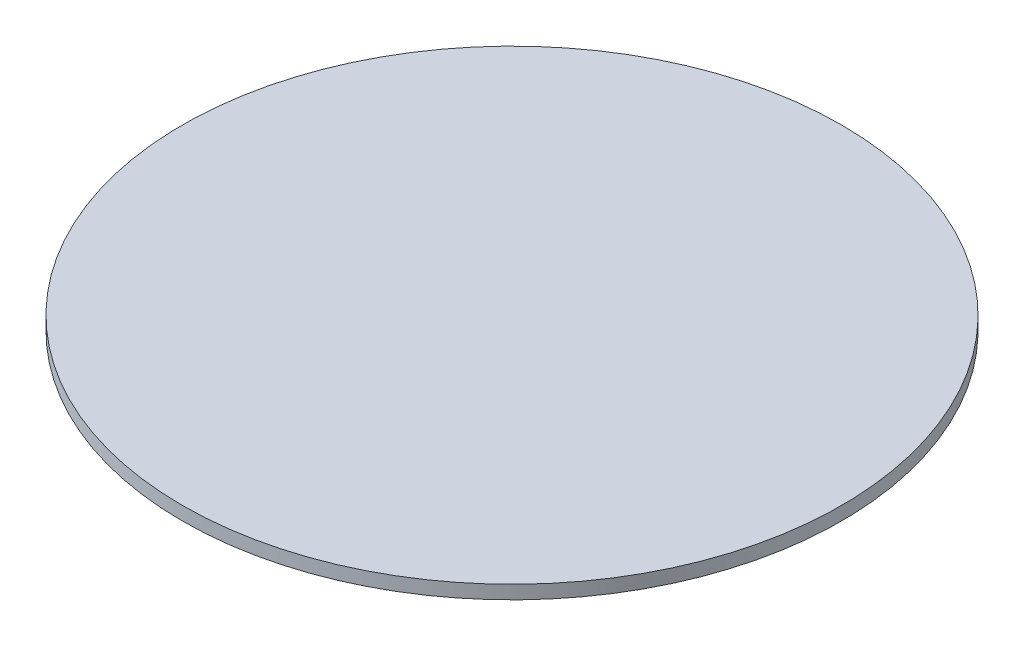
SolidWorks part; units mm, degrees
ref_plane "Front Plane" through (0, 0, 0) normal (0, 0, 1) x (1, 0, 0)
ref_plane "Top Plane" through (0, 0, 0) normal (0, 1, 0) x (1, 0, 0)
ref_plane "Right Plane" through (0, 0, 0) normal (1, 0, 0) x (0, 0, -1)
sketch "Sketch1" plane through (0, 0, 0) normal (0, 1, 0) x (1, 0, 0)
  circle A0 centre (0, 0) radius 73.2
  dimension "D1" = 146.4
extrude "Boss-Extrude1" add sketch "Sketch1" along normal blind 3
